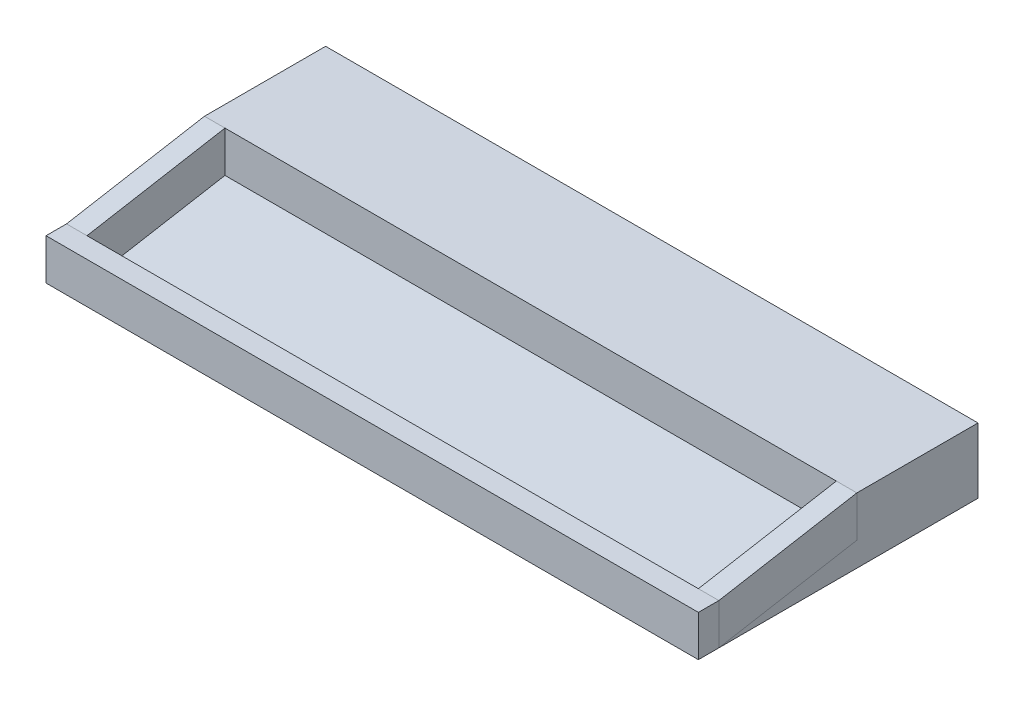
SolidWorks part; units mm, degrees
ref_plane "Plan de face" through (0, 0, 0) normal (0, 0, 1) x (1, 0, 0)
ref_plane "Plan de dessus" through (0, 0, 0) normal (0, 1, 0) x (1, 0, 0)
ref_plane "Plan de droite" through (0, 0, 0) normal (1, 0, 0) x (0, 0, -1)
sketch "Esquisse1" plane through (0, 0, 0) normal (1, 0, 0) x (0, 0, -1)
  line L0 (-57.9785, -18.5466) -> (-206.0126, -44.5466)
  line L1 (72.0215, 25.4534) -> (-57.9785, 25.4534)
  line L2 (72.0215, 25.4534) -> (72.0215, -44.5466)
  line L3 (72.0215, -44.5466) -> (-57.9785, -44.5466)
  line L4 (-57.9785, 25.4534) -> (-57.9785, -44.5466)
  line L5 (-206.0126, -44.5466) -> (-57.9785, -44.5466)
  line L6 (-57.9785, 3.4534) -> (72.0215, 3.4534)
  line L8 (-206.0126, -44.5466) -> (-228.0126, -44.5466)
  line L9 (-206.0126, -44.5466) -> (-206.0126, -22.5466)
  line L10 (-206.0126, -22.5466) -> (-228.0126, -22.5466)
  line L11 (-228.0126, -44.5466) -> (-228.0126, -22.5466)
  line L12 (-206.0126, -22.5466) -> (-228.0126, -22.5466)
  line L13 (-206.0126, -22.5466) -> (-206.0126, -0.5466)
  line L14 (-206.0126, -0.5466) -> (-228.0126, -0.5466)
  line L15 (-228.0126, -22.5466) -> (-228.0126, -0.5466)
  point P4 (-57.9785, -18.5466)
  dimension "D1" = 70
  dimension "D2" = 130
  dimension "D3" = 22
  dimension "D4" = 22
  dimension "D5" = 150.3
  dimension "D6" = 22
  dimension "D7" = 22
  dimension "D8" = 22
extrude "Boss.-Extru.1" add sketch "Esquisse1" along normal blind 700 contours L4 L6 L2 L1 | L6 L4 L3 L2 | L0 L5 L4 | L11 L8 L9 L10 | L15 L10 L13 L14
sketch "Esquisse2" plane through (700, 0, 0) normal (1, 0, 0) x (0, 0, -1)
  line L0 (-57.9785, 25.4534) -> (-206.0126, -0.5466)
  line L1 (-206.0126, -0.5466) -> (-206.0126, -44.5466)
  line L2 (-206.0126, -44.5466) -> (-57.9785, -18.5466)
  line L3 (-57.9785, -18.5466) -> (-57.9785, 25.4534)
extrude "Boss.-Extru.5" add sketch "Esquisse2" against normal blind 22 separate body
sketch "Esquisse3" plane through (0, 0, 0) normal (-1, 0, 0) x (0, 0, 1)
  line L0 (57.9785, 25.4534) -> (206.0126, -0.5466)
  line L1 (206.0126, -0.5466) -> (206.0126, -44.5466)
  line L2 (206.0126, -44.5466) -> (57.9785, -18.5466)
  line L3 (57.9785, -18.5466) -> (206.0126, -44.5466) construction
  line L4 (57.9785, 25.4534) -> (57.9785, -18.5466) construction
  line L5 (57.9785, -18.5466) -> (57.9785, 25.4534)
extrude "Boss.-Extru.7" add sketch "Esquisse3" against normal blind 22 separate body
